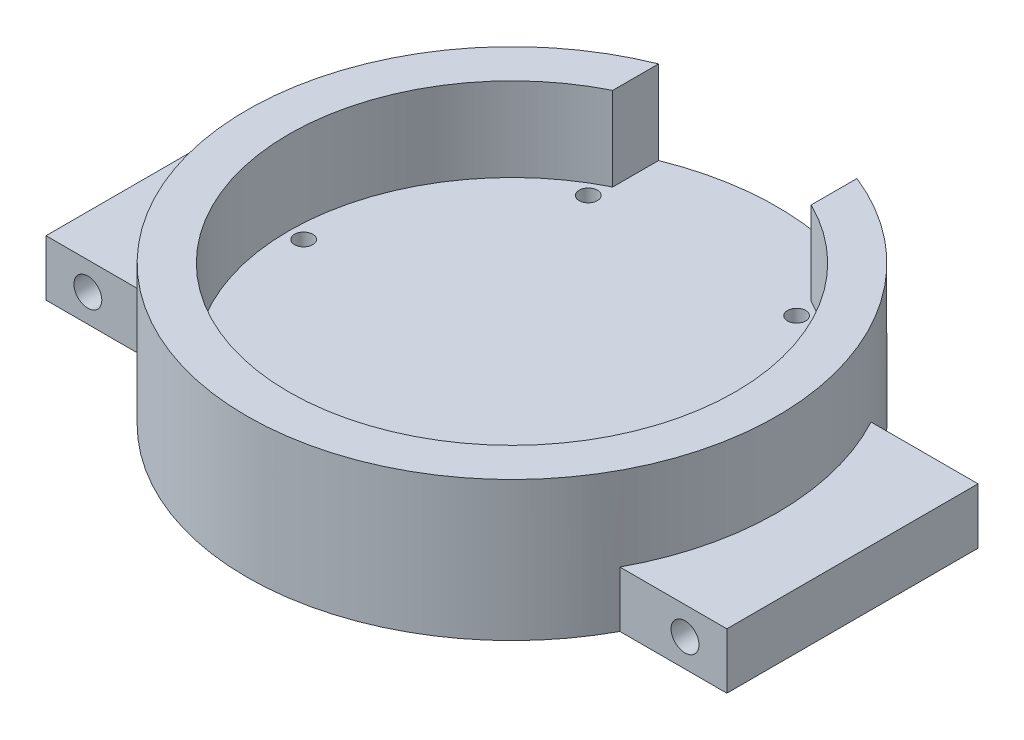
SolidWorks part; units mm, degrees
ref_plane "Front Plane" through (0, 0, 0) normal (0, 0, 1) x (1, 0, 0)
ref_plane "Top Plane" through (0, 0, 0) normal (0, 1, 0) x (1, 0, 0)
ref_plane "Right Plane" through (0, 0, 0) normal (1, 0, 0) x (0, 0, -1)
sketch "Sketch7" plane through (0, 0, 0) normal (0, 1, 0) x (1, 0, 0)
  line L1 (-61, 0) -> (61, 0)
  line L2 (-61, 0) -> (-61, 45)
  line L3 (-61, 45) -> (61, 45)
  line L4 (61, 0) -> (61, 45)
  dimension "D1" = 45
  dimension "D2" = 122
extrude "Boss-Extrude1" add sketch "Sketch7" along normal blind 10
sketch "Sketch9" plane through (0, 10, 0) normal (0, 1, 0) x (1, 0, 0)
  line L0 (-61, 45) -> (-61, 0) construction
  circle A0 centre (0, 22.5) radius 37.333 construction
  circle A1 centre (0, 22.5) radius 42.333
  circle A2 centre (-37.333, 22.5) radius 2.5
  circle A3 centre (-18.6665, 54.8313) radius 2.5
  circle A4 centre (18.6665, 54.8313) radius 2.5
  circle A5 centre (37.333, 22.5) radius 2.5
  circle A6 centre (18.6665, -9.8313) radius 2.5
  circle A7 centre (-18.6665, -9.8313) radius 2.5
  point P6 (-61, 22.5)
  line M5 (-61, 0) -> (61, 0)
  line M7 (61, 45) -> (-61, 45)
  dimension "D1" = 74.666
  dimension "D2" = 5
  dimension "D3" = 5
  dimension "D4" = 6
extrude "Boss-Extrude2" add sketch "Sketch9" against normal up to surface (10 mm away) contours A1 A5 A2 M5 M7 | A5 | A2 | A1 A7 A6 M5 | A6 | A7 | A4 | A1 A4 A3 M7 | A3 up to face at (0, 0, -22.5)
sketch "Sketch10" plane through (0, 0, 0) normal (0, -1, 0) x (1, 0, 0)
  circle A0 centre (0, -22.5) radius 40
  arc A1 (35.8585, 0) -> (-35.8585, 0) centre (0, -22.5) ccw construction
  circle A2 centre (0, -22.5) radius 47.5
  line M5 (-61, -45) -> (-35.8585, -45)
  arc M6 (-35.8585, -45) -> (35.8585, -45) centre (0, -22.5) ccw
  line M7 (35.8585, -45) -> (61, -45)
  line M9 (61, 0) -> (35.8585, 0)
  arc M10 (35.8585, 0) -> (-35.8585, 0) centre (0, -22.5) ccw
  line M11 (-35.8585, 0) -> (-61, 0)
  dimension "D1" = 80
  dimension "D2" = 7.5
extrude "Boss-Extrude3" add sketch "Sketch10" against normal blind 25 contours A2 M5 M7 M6 | A2 A0 M7 M9 M10 M11 M5 M6 | A2 M9 M11 M10
sketch "Sketch11" plane through (0, 0, 0) normal (0, 0, 1) x (1, 0, 0)
  line L0 (61, 10) -> (61, 0) construction
  line L1 (-61, 10) -> (-61, 0) construction
  circle A0 centre (-53.5, 5) radius 2.5
  circle A1 centre (53.5, 5) radius 2.5
  point P8 (-61, 5)
  dimension "D2" = 5
  dimension "D1" = 7.5
  dimension "D3" = 7.5
extrude "Cut-Extrude5" cut sketch "Sketch11" against normal through all
sketch "Sketch12" plane through (0, 10, 0) normal (0, 1, 0) x (1, 0, 0)
  line L0 (-17.78, 58.3312) -> (-17.78, 66.5468)
  line L1 (17.78, 58.3312) -> (17.78, 66.5468)
  arc A0 (17.78, 58.3312) -> (-17.78, 58.3312) centre (0, 22.5) ccw
  circle A1 centre (0, 22.5) radius 40 construction
  arc A2 (17.78, 66.5468) -> (-17.78, 66.5468) centre (0, 22.5) ccw
  circle A3 centre (0, 22.5) radius 47.5 construction
  circle A4 centre (0, 22.5) radius 40 construction
  point P1 (0, 62.5)
  dimension "D1" = 35.56
extrude "Cut-Extrude6" cut sketch "Sketch12" along normal through all
hole_wizard "CSK for #4 Flat Head Socket Cap Screw1" positions "Sketch13" profile "Sketch14" countersink size "#4" standard "ANSI Inch"
sketch "Sketch13" plane through (0, 10, 0) normal (0, 1, 0) x (1, 0, 0)
  point P0 (-18.6665, 54.8313)
  point P3 (-37.333, 22.5)
  point P6 (-18.6665, -9.8313)
  point P9 (18.6665, -9.8313)
  point P12 (37.333, 22.5)
  point P15 (18.6665, 54.8313)
sketch "Sketch14" plane through (-18.6665, 10, -54.8313) normal (1, 0, 0) x (0, 0, 1)
  line L0 (0, 0) -> (0, 10)
  line L1 (0, 10) -> (1.6319, 10)
  line L2 (1.6319, 10) -> (1.6319, 1.8481)
  line L3 (1.6319, 1.8481) -> (3.2385, 0)
  line L5 (3.2385, 0) -> (0, 0)
  line L6 (-1.6319, 1.8481) -> (-3.2385, 0) construction
  line L11 (0, -6.35) -> (0, 107.95) construction
  dimension "Thru Hole Dia." = 3.2639
  dimension "Thru Hole Depth" = 10
  dimension "Near C'Sink Dia." = 6.477
  dimension "Near C'Sink Angle" = 82
sketch "Sketch15" plane through (0, 0, 0) normal (0, -1, 0) x (1, 0, 0)
  point P0 (-18.6665, 9.8313)
  point P1 (18.6665, 9.8313)
  point P3 (37.333, -22.5)
  point P5 (18.6665, -54.8313)
  point P7 (-18.6665, -54.8313)
  point P9 (-37.333, -22.5)
hole_wizard "CBORE for #4 Binding Head Machine Screw1" positions "Sketch15" profile "Sketch17" counterbore size "#4" standard "ANSI Inch" end condition through all
sketch "Sketch17" plane through (-18.6665, 0, 9.8313) normal (1, 0, 0) x (0, 0, -1)
  line L0 (0, 0) -> (0, 25)
  line L1 (0, 25) -> (1.6319, 25)
  line L3 (1.6319, 25) -> (1.6319, 1.7272)
  line L4 (1.6319, 1.7272) -> (3.3731, 1.7272)
  line L5 (3.3731, 1.7272) -> (3.3731, 0)
  line L7 (3.3731, 0) -> (0, 0)
  line L11 (0, -6.35) -> (0, 107.95) construction
  dimension "Thru Hole Dia." = 3.2639
  dimension "Thru Hole Depth" = 25
  dimension "C'Bore Dia." = 6.7462
  dimension "C'Bore Depth" = 1.7272
